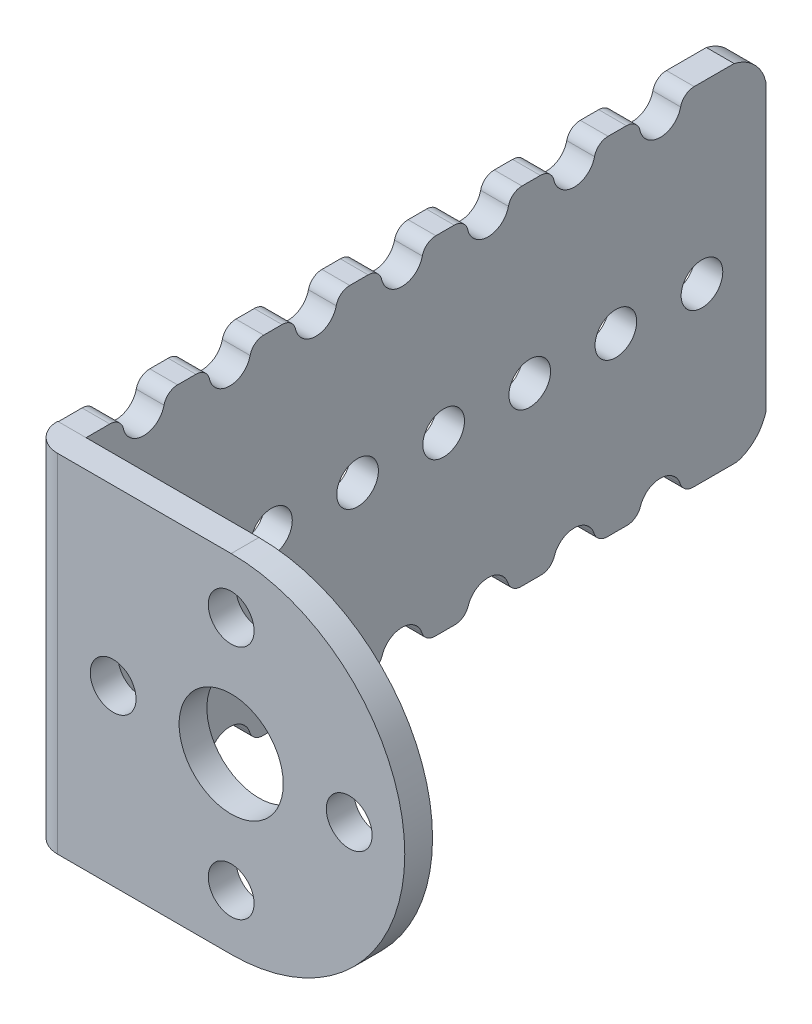
SolidWorks part; units mm, degrees
ref_plane "Alzado" through (0, 0, 0) normal (0, 0, 1) x (1, 0, 0)
ref_plane "Planta" through (0, 0, 0) normal (0, 1, 0) x (1, 0, 0)
ref_plane "Vista lateral" through (0, 0, 0) normal (1, 0, 0) x (0, 0, -1)
sketch "Croquis1" plane through (0, 0, 0) normal (0, 0, 1) x (1, 0, 0)
  line L0 (0, 0) -> (0, 25)
  line L1 (0, 0) -> (14.5, 0)
  line L2 (0, 25) -> (14.5, 25)
  line L3 (0, 12.5) -> (14.5, 12.5) construction
  line L4 (14.5, 12.5) -> (14.5, 25) construction
  line L5 (0, 12.5) -> (27, 12.5) construction
  circle A0 centre (14.5, 12.5) radius 3.75
  circle A1 centre (14.5, 21) radius 1.65
  circle A2 centre (23, 12.5) radius 1.65
  circle A3 centre (14.5, 4) radius 1.65
  circle A4 centre (6, 12.5) radius 1.65
  arc A5 (14.5, 25) -> (14.5, 0) centre (14.5, 12.5) cw
  dimension "D1" = 25
  dimension "D2" = 14.5
  dimension "D3" = 7.5
  dimension "D4" = 3.3
  dimension "D5" = 3.3
  dimension "D6" = 3.3
  dimension "D7" = 3.3
  dimension "D8" = 27
extrude "Saliente-Extruir1" add sketch "Croquis1" along normal blind 2
sketch "Croquis4" plane through (0, 0, 0) normal (-1, 0, 0) x (0, 0, 1)
  line L0 (-45.3169, 24.95) -> (-45.3169, 0) construction
  line L1 (2, 0) -> (-46.9228, 0)
  line L2 (2, 0) -> (2, 24.95)
  line L3 (2, 24.95) -> (-46.7155, 24.95)
  line L4 (-49, 2.0772) -> (-49, 22.6655)
  arc A0 (-46.7155, 24.95) -> (-49, 22.6655) centre (-46.0162, 21.9662) ccw
  arc A1 (-46.9228, 0) -> (-49, 2.0772) centre (-46.1199, 2.8801) cw
extrude "Saliente-Extruir2" add sketch "Croquis4" against normal blind 2
sketch "Croquis5" plane through (2, 0, 0) normal (1, 0, 0) x (0, 0, -1)
  line L0 (49, 12.3713) -> (44.4, 12.3713) construction
  line L1 (49, 22.6655) -> (49, 2.0772) construction
  line L2 (44.4, 12.3713) -> (38.2, 12.3713) construction
  line L3 (38.2, 12.3713) -> (32, 12.3713) construction
  line L4 (32, 12.3713) -> (25.8, 12.3713) construction
  line L5 (25.8, 12.3713) -> (19.6, 12.3713) construction
  line L6 (19.6, 12.3713) -> (13.4, 12.3713) construction
  line L7 (13.4, 12.3713) -> (7.2, 12.3713) construction
  line L8 (4.2, 24.5) -> (10.4, 24.5) construction
  line L11 (-2, 12.5) -> (-2, 24.5) construction
  line L12 (-2, 25) -> (-2, 0) construction
  line L13 (-2, 12.5) -> (-2, 0.5) construction
  line L14 (-2, 24.5) -> (4.2, 24.5) construction
  line L15 (10.4, 24.5) -> (16.6, 24.5) construction
  line L16 (16.6, 24.5) -> (22.8, 24.5) construction
  line L17 (22.8, 24.5) -> (29, 24.5) construction
  line L18 (29, 24.5) -> (35.2, 24.5) construction
  line L19 (35.2, 24.5) -> (41.4, 24.5) construction
  circle A0 centre (44.4, 12.3713) radius 1.5
  circle A1 centre (38.2, 12.3713) radius 1.5
  circle A2 centre (32, 12.3713) radius 1.5
  circle A3 centre (25.8, 12.3713) radius 1.5
  circle A4 centre (19.6, 12.3713) radius 1.5
  circle A5 centre (13.4, 12.3713) radius 1.5
  circle A6 centre (7.2, 12.3713) radius 1.5
  circle A7 centre (4.2, 24.5) radius 1.5
  circle A8 centre (10.4, 24.5) radius 1.5
  circle A9 centre (16.6, 24.5) radius 1.5
  circle A10 centre (22.8, 24.5) radius 1.5
  circle A11 centre (29, 24.5) radius 1.5
  circle A12 centre (35.2, 24.5) radius 1.5
  circle A13 centre (41.4, 24.5) radius 1.5
  circle A15 centre (41.4, 0.2427) radius 1.5
  circle A16 centre (35.2, 0.2427) radius 1.5
  circle A17 centre (29, 0.2427) radius 1.5
  circle A18 centre (22.8, 0.2427) radius 1.5
  circle A19 centre (16.6, 0.2427) radius 1.5
  circle A20 centre (10.4, 0.2427) radius 1.5
  circle A21 centre (4.2, 0.2427) radius 1.5
  point P50 (0, 0)
  point P51 (0, 0)
  dimension "D2" = 3
  dimension "D4" = 6.2
  dimension "D6" = 3
  dimension "D7" = 3
  dimension "D8" = 3
  dimension "D12" = 3
  dimension "D13" = 3
  dimension "D14" = 3
  dimension "D18" = 3
  dimension "D20" = 3
  dimension "D23" = 6.2
  dimension "D25" = 3
  dimension "D26" = 3
  dimension "D27" = 3
  dimension "D28" = 3
  dimension "D29" = 3
  dimension "D1" = 4.6
  dimension "D3" = 6.2
  dimension "D5" = 6.2
  dimension "D9" = 6.2
  dimension "D10" = 6.2
  dimension "D11" = 6.2
  dimension "D15" = 6.2
  dimension "D16" = 12
  dimension "D17" = 12
  dimension "D19" = 6.2
  dimension "D21" = 6.2
  dimension "D22" = 6.2
  dimension "D24" = 6.2
  dimension "D30" = 6.2
extrude "Cortar-Extruir2" cut sketch "Croquis5" against normal blind 10
fillet "Redondeo3" radius 1 2 edges at (1, 24.95, -8.9691) (1, 24.95, -5.6309)
fillet "Redondeo4" radius 1 4 edges at (1, 24.95, -21.3691) (1, 24.95, -15.1691) (1, 24.95, -18.0309) (1, 24.95, -11.8309)
fillet "Redondeo5" radius 1 7 edges at (1, 24.95, -39.9691) (1, 24.95, -42.8309) (1, 24.95, -33.7691) (1, 24.95, -36.6309) (1, 24.95, -27.5691) (1, 24.95, -30.4309) (1, 24.95, -24.2309)
fillet "Redondeo6" radius 1 1 edges at (1, 24.95, -2.7691)
fillet "Redondeo7" radius 1 9 edges at (1, 0, -27.5198) (1, 0, -24.2802) (1, 0, -21.3198) (1, 0, -18.0802) (1, 0, -15.1198) (1, 0, -11.8802) (1, 0, -8.9198) (1, 0, -5.6802) (1, 0, -2.7198)
fillet "Redondeo8" radius 1 5 edges at (1, 0, -42.8802) (1, 0, -39.9198) (1, 0, -36.6802) (1, 0, -33.7198) (1, 0, -30.4802)
fillet "Redondeo12" radius 2 1 edges at (0, 12.5, 2)
